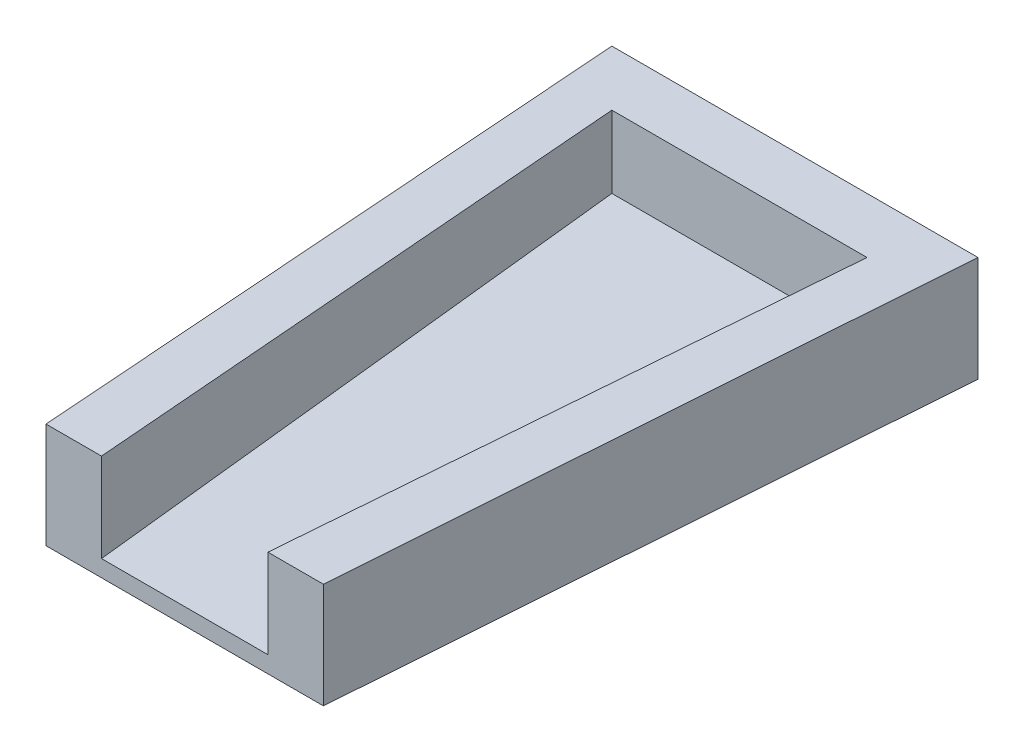
SolidWorks part; units mm, degrees
ref_plane "Plano frontal" through (0, 0, 0) normal (0, 0, 1) x (1, 0, 0)
ref_plane "Plano superior" through (0, 0, 0) normal (0, 1, 0) x (1, 0, 0)
ref_plane "Plano direito" through (0, 0, 0) normal (1, 0, 0) x (0, 0, -1)
sketch "Esboço1" plane through (0, 0, 0) normal (0, 0, 1) x (1, 0, 0)
  line L1 (-3.3, -1.9) -> (3.3, -1.9)
  line L2 (-3.3, -1.9) -> (-3.3, 1.9)
  line L3 (-3.3, 1.9) -> (3.3, 1.9)
  line L4 (3.3, -1.9) -> (3.3, 1.9)
  line L5 (-3.3, -1.9) -> (3.3, 1.9) construction
  line L6 (-3.3, 1.9) -> (3.3, -1.9) construction
  point P0 (0, 0)
  dimension "D1" = 6.6
  dimension "D2" = 3.8
ref_plane "Plano1" through (0, 0, 11) normal (0, 0, 1) x (1, 0, 0)
sketch "Esboço2" plane through (0, 0, 11) normal (0, 0, 1) x (1, 0, 0)
  line L1 (-2.5, -1.9) -> (2.5, -1.9)
  line L2 (-2.5, -1.9) -> (-2.5, 1.9)
  line L3 (-2.5, 1.9) -> (2.5, 1.9)
  line L4 (2.5, -1.9) -> (2.5, 1.9)
  line L5 (-2.5, -1.9) -> (2.5, 1.9) construction
  line L6 (-2.5, 1.9) -> (2.5, -1.9) construction
  point P0 (0, 0)
  dimension "D1" = 5
  dimension "D2" = 3.8
loft "Loft1" add profiles "Esboço1", "Esboço2"
sketch "Esboço3" plane through (0, 0, 0) normal (0, 0, 1) x (1, 0, 0)
  line L1 (-4.3618, 0) -> (6.3395, 0)
  line L2 (-4.3618, 0) -> (-4.3618, 3.7794)
  line L3 (-4.3618, 3.7794) -> (6.3395, 3.7794)
  line L4 (6.3395, 0) -> (6.3395, 3.7794)
  point P4 (6.3395, 3.7794)
extrude "Corte Meio" cut sketch "Esboço3" against normal through all and the other way through all
sketch "Esboço4" plane through (0, 0, 0) normal (0, 1, 0) x (1, 0, 0)
  line L0 (0, 0.9336) -> (0, -10.4175) construction
  line L1 (-2.3, -1) -> (2.3, -1)
  line L3 (-1.5, -11) -> (1.5, -11)
  line L4 (-1.1001, -11) -> (1.1001, -11) construction
  line L5 (-2.3, -1) -> (-1.5, -11)
  line L6 (2.3, -1) -> (1.5, -11)
  point P6 (0, -1)
  point P8 (0, 0)
  point P13 (0, -11)
  dimension "D1" = 4.6
  dimension "D2" = 3
  dimension "D3" = 10
extrude "Corte-extrusão2" [suppressed] cut sketch "Esboço4" against normal blind 1.2
ref_plane "Plano2" through (0, 0, 1) normal (0, 0, 1) x (1, 0, 0)
sketch "Esboço5" plane through (0, 0, 1) normal (0, 0, 1) x (1, 0, 0)
  line L1 (2.3, -1.3) -> (-2.3, -1.3)
  line L2 (2.3, -1.3) -> (2.3, 1.3)
  line L3 (2.3, 1.3) -> (-2.3, 1.3)
  line L4 (-2.3, -1.3) -> (-2.3, 1.3)
  line L5 (2.3, -1.3) -> (-2.3, 1.3) construction
  line L6 (2.3, 1.3) -> (-2.3, -1.3) construction
  point P0 (0, 0)
  dimension "D1" = 4.6
  dimension "D2" = 2.6
sketch "Esboço6" plane through (0, 0, 11) normal (0, 0, 1) x (1, 0, 0)
  line L1 (-1.5, -1.6) -> (1.5, -1.6)
  line L2 (-1.5, -1.6) -> (-1.5, 1.6)
  line L3 (-1.5, 1.6) -> (1.5, 1.6)
  line L4 (1.5, -1.6) -> (1.5, 1.6)
  line L5 (-1.5, -1.6) -> (1.5, 1.6) construction
  line L6 (-1.5, 1.6) -> (1.5, -1.6) construction
  line L7 (2.5, 0) -> (-2.5, 0) construction
  point P0 (0, 0)
  dimension "D1" = 3.2
  dimension "D2" = 0
  dimension "D3" = 3
loft "Loft de corte1" cut profiles "Esboço6", "Esboço5"
